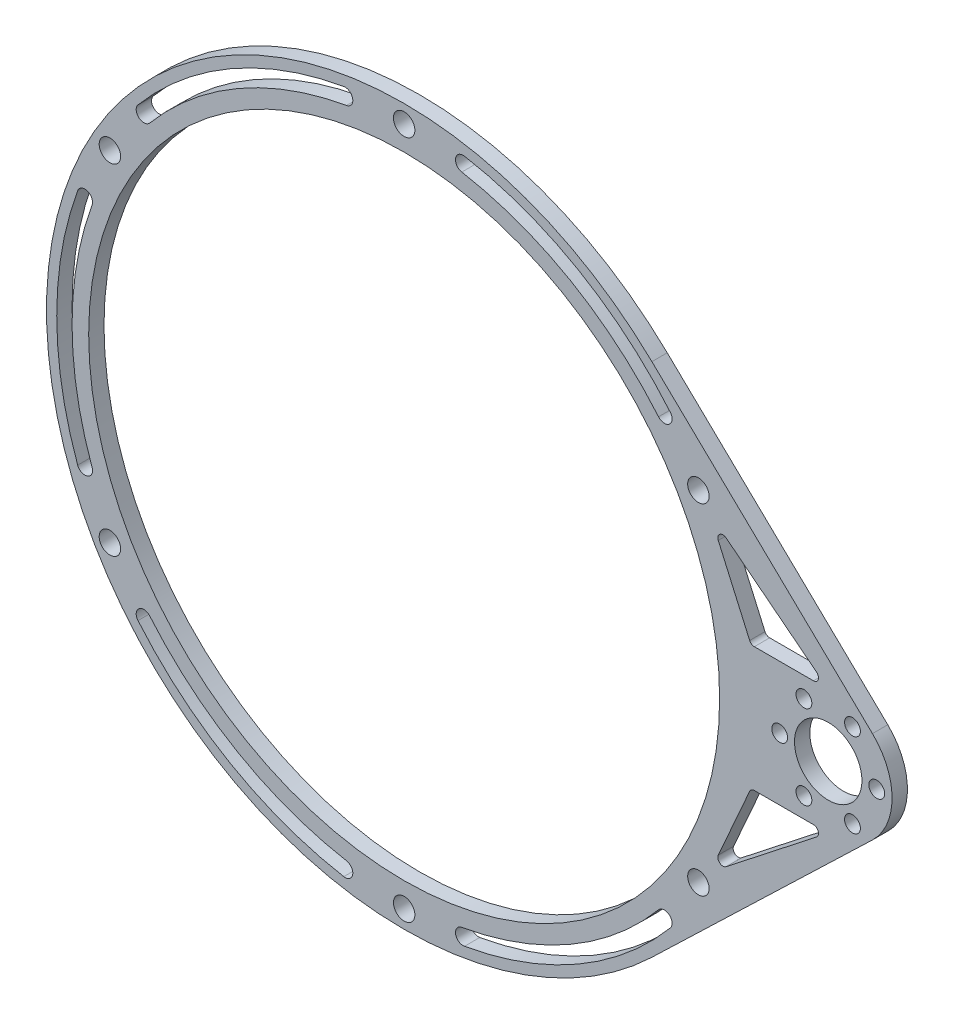
SolidWorks part; units mm, degrees
material "Hexcel AS4C (3000 丝)"
ref_plane "前视基准面" through (0, 0, 0) normal (0, 0, 1) x (1, 0, 0)
ref_plane "上视基准面" through (0, 0, 0) normal (0, 1, 0) x (1, 0, 0)
ref_plane "右视基准面" through (0, 0, 0) normal (1, 0, 0) x (0, 0, -1)
other "Configuration Table"
sketch "草图1" plane through (0, 0, 0) normal (0, 0, 1) x (1, 0, 0)
  line L0 (0, 0) -> (83, 0) construction
  line L1 (48.494, 50.481) -> (91.6596, 9.0145)
  line L2 (91.6596, -9.0145) -> (48.494, -50.481)
  circle A0 centre (0, 0) radius 66.5 construction
  circle A1 centre (0, 66.5) radius 2.1
  circle A2 centre (57.5907, 33.25) radius 2.1
  circle A3 centre (57.5907, -33.25) radius 2.1
  circle A4 centre (0, -66.5) radius 2.1
  circle A5 centre (-57.5907, -33.25) radius 2.1
  circle A6 centre (-57.5907, 33.25) radius 2.1
  circle A7 centre (0, 0) radius 61.75
  circle A8 centre (0, 0) radius 70
  circle A9 centre (83, 0) radius 9.5 construction
  circle A10 centre (92.5, 0) radius 1.55
  circle A11 centre (87.75, -8.2272) radius 1.55
  circle A12 centre (78.25, -8.2272) radius 1.55
  circle A13 centre (83, 0) radius 12.5
  circle A14 centre (83, 0) radius 6.6
  circle A15 centre (73.5, 0) radius 1.55
  circle A16 centre (78.25, 8.2272) radius 1.55
  circle A17 centre (87.75, 8.2272) radius 1.55
  point P18 (0, 0)
  point P29 (83, 0)
  dimension "D1" = 133
  dimension "D2" = 4.2
  dimension "D4" = 123.5
  dimension "D5" = 140
  dimension "D7" = 19
  dimension "D9" = 3.1
  dimension "D10" = 25
  dimension "D11" = 13.2
  dimension "D6" = 83
  dimension "D3" = 6
  dimension "D8" = 6
extrude "凸台-拉伸1" add sketch "草图1" along normal blind 3 contours A8 A1 A2 A3 A4 A5 A6 A7 | A13 L1 A8 L2 | A13 A10 A11 A12
sketch "草图2" plane through (0, 0, 3) normal (0, 0, 1) x (1, 0, 0)
  line L0 (0, 0) -> (83, 0) construction
  line L1 (59.8592, 30.3389) -> (67.8899, 12.1895)
  line L2 (67.8899, 12.1895) -> (83, 12.1895)
  line L3 (83, 12.1895) -> (59.8592, 30.3389)
  line L4 (67.8899, -12.1895) -> (83, -12.1895)
  line L5 (59.8592, -30.3389) -> (67.8899, -12.1895)
  line L6 (83, -12.1895) -> (59.8592, -30.3389)
extrude "切除-拉伸1" cut sketch "草图2" against normal through all
fillet "圆角1" radius 1 6 edges at (83, -12.1895, 1.5) (59.8592, -30.3389, 1.5) (67.8899, -12.1895, 1.5) (67.8899, 12.1895, 1.5) (83, 12.1895, 1.5) (59.8592, 30.3389, 1.5)
sketch "草图3" plane through (0, 0, 3) normal (0, 0, 1) x (1, 0, 0)
  line L0 (0, 0) -> (33.25, 57.5907) construction
  line L1 (0, 0) -> (35.8352, 0) construction
  circle A0 centre (0, 0) radius 66.5 construction
  arc A1 (11.5476, 65.4897) -> (50.942, 42.7454) centre (0, 0) cw construction
  arc A2 (52.091, 43.7096) -> (11.8081, 66.9669) centre (0, 0) ccw
  arc A3 (49.7929, 41.7812) -> (11.2871, 64.0125) centre (0, 0) ccw
  arc A4 (49.7929, 41.7812) -> (52.091, 43.7096) centre (50.942, 42.7454) ccw
  arc A5 (11.8081, 66.9669) -> (11.2871, 64.0125) centre (11.5476, 65.4897) ccw
  arc A10 (62.4896, 22.7443) -> (62.4896, -22.7443) centre (0, 0) cw construction
  arc A11 (11.2871, -64.0125) -> (49.7929, -41.7812) centre (0, 0) ccw
  arc A12 (11.2871, -64.0125) -> (11.8081, -66.9669) centre (11.5476, -65.4897) ccw
  arc A13 (52.091, -43.7096) -> (49.7929, -41.7812) centre (50.942, -42.7454) ccw
  arc A14 (11.8081, -66.9669) -> (52.091, -43.7096) centre (0, 0) ccw
  arc A15 (50.942, -42.7454) -> (11.5476, -65.4897) centre (0, 0) cw construction
  arc A16 (-49.7929, -41.7812) -> (-11.2871, -64.0125) centre (0, 0) ccw
  arc A17 (-49.7929, -41.7812) -> (-52.091, -43.7096) centre (-50.942, -42.7454) ccw
  arc A18 (-11.8081, -66.9669) -> (-11.2871, -64.0125) centre (-11.5476, -65.4897) ccw
  arc A19 (-52.091, -43.7096) -> (-11.8081, -66.9669) centre (0, 0) ccw
  arc A20 (-11.5476, -65.4897) -> (-50.942, -42.7454) centre (0, 0) cw construction
  arc A21 (-61.08, 22.2313) -> (-61.08, -22.2313) centre (0, 0) ccw
  arc A22 (-61.08, 22.2313) -> (-63.8991, 23.2574) centre (-62.4896, 22.7443) ccw
  arc A23 (-63.8991, -23.2574) -> (-61.08, -22.2313) centre (-62.4896, -22.7443) ccw
  arc A24 (-63.8991, 23.2574) -> (-63.8991, -23.2574) centre (0, 0) ccw
  arc A25 (-62.4896, -22.7443) -> (-62.4896, 22.7443) centre (0, 0) cw construction
  arc A26 (-11.2871, 64.0125) -> (-49.7929, 41.7812) centre (0, 0) ccw
  arc A27 (-11.2871, 64.0125) -> (-11.8081, 66.9669) centre (-11.5476, 65.4897) ccw
  arc A28 (-52.091, 43.7096) -> (-49.7929, 41.7812) centre (-50.942, 42.7454) ccw
  arc A29 (-11.8081, 66.9669) -> (-52.091, 43.7096) centre (0, 0) ccw
  arc A30 (-50.942, 42.7454) -> (-11.5476, 65.4897) centre (0, 0) cw construction
  arc A31 (61.08, -22.2313) -> (61.08, 22.2313) centre (0, 0) ccw [skipped]
  arc A32 (61.08, -22.2313) -> (63.8991, -23.2574) centre (62.4896, -22.7443) ccw [skipped]
  arc A33 (63.8991, 23.2574) -> (61.08, 22.2313) centre (62.4896, 22.7443) ccw [skipped]
  arc A34 (63.8991, -23.2574) -> (63.8991, 23.2574) centre (0, 0) ccw [skipped]
  point P7 (33.25, 57.5907)
  point P19 (66.5, 0)
  point P26 (33.25, -57.5907)
  point P33 (-33.25, -57.5907)
  point P40 (-66.5, 0)
  point P47 (-33.25, 57.5907)
  point P52 (0, 0)
  dimension "D1" = 1.5
  dimension "D2" = 40
  dimension "D3" = 60
  dimension "D4" = 6
extrude "切除-拉伸2" cut sketch "草图3" against normal through all
